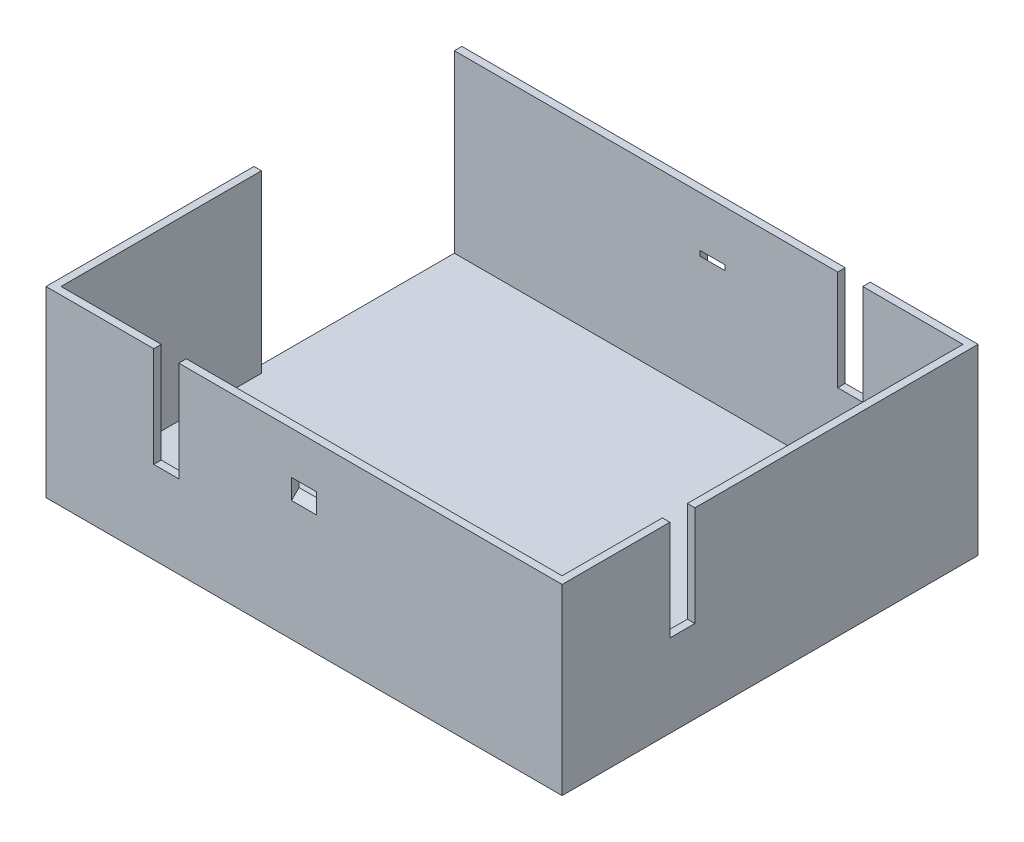
SolidWorks part; units mm, degrees
ref_plane "Front Plane" through (0, 0, 0) normal (0, 0, 1) x (1, 0, 0)
ref_plane "Top Plane" through (0, 0, 0) normal (0, 1, 0) x (1, 0, 0)
ref_plane "Right Plane" through (0, 0, 0) normal (1, 0, 0) x (0, 0, -1)
sketch "Sketch1" plane through (0, 0, 0) normal (0, 1, 0) x (1, 0, 0)
  line L1 (-28.4717, 11.6745) -> (74.5283, 11.6745)
  line L2 (-28.4717, 11.6745) -> (-28.4717, -71.3255)
  line L3 (-28.4717, -71.3255) -> (74.5283, -71.3255)
  line L4 (74.5283, 11.6745) -> (74.5283, -71.3255)
  dimension "D1" = 103
  dimension "D2" = 83
extrude "Boss-Extrude1" add sketch "Sketch1" along normal blind 1.5
sketch "Sketch2" plane through (0, 1.5, 0) normal (0, 1, 0) x (1, 0, 0)
  line L0 (-26.9717, 10.1745) -> (-26.9717, -69.8255)
  line L1 (-28.4717, 11.6745) -> (74.5283, 11.6745)
  line L2 (-28.4717, 11.6745) -> (-28.4717, -71.3255)
  line L3 (-28.4717, -71.3255) -> (74.5283, -71.3255)
  line L4 (74.5283, 11.6745) -> (74.5283, -71.3255)
  line L5 (-26.9717, -69.8255) -> (73.0283, -69.8255)
  line L6 (73.0283, 10.1745) -> (73.0283, -69.8255)
  line L7 (-26.9717, 10.1745) -> (73.0283, 10.1745)
  dimension "D1" = 1.5
extrude "Boss-Extrude2" add sketch "Sketch2" along normal blind 35
sketch "Sketch4" plane through (-28.4717, 0, 0) normal (-1, 0, 0) x (0, 0, 1)
  line L0 (-10.1745, 1.5) -> (69.8255, 1.5) construction
  line L1 (-10.1745, 36.5) -> (29.8255, 36.5)
  line L2 (-10.1745, 36.5) -> (-10.1745, 1.5)
  line L3 (-10.1745, 1.5) -> (29.8255, 1.5)
  line L4 (29.8255, 36.5) -> (29.8255, 1.5)
  dimension "D1" = 40
extrude "Cut-Extrude2" cut sketch "Sketch4" against normal blind 1.5
sketch "Sketch5" plane through (0, 0, 71.3255) normal (0, 0, 1) x (1, 0, 0)
  line L1 (-28.4717, 36.5) -> (74.5283, 36.5) construction
  line L2 (-6.9717, 36.5) -> (-1.9717, 36.5)
  line L3 (-6.9717, 36.5) -> (-6.9717, 16.5)
  line L4 (-6.9717, 16.5) -> (-1.9717, 16.5)
  line L7 (-1.9717, 36.5) -> (-1.9717, 16.5)
  line L8 (-26.9717, 36.5) -> (-26.9717, 1.5) construction
  dimension "D1" = 5
  dimension "D2" = 20
  dimension "D3" = 20
extrude "Cut-Extrude3" cut sketch "Sketch5" against normal blind 1.5
sketch "Sketch6" plane through (74.5283, 0, 0) normal (1, 0, 0) x (0, 0, -1)
  line L0 (-71.3255, 36.5) -> (11.6745, 36.5) construction
  line L1 (-49.8255, 36.5) -> (-44.8255, 36.5)
  line L2 (-49.8255, 36.5) -> (-49.8255, 16.5)
  line L3 (-49.8255, 16.5) -> (-44.8255, 16.5)
  line L4 (-44.8255, 36.5) -> (-44.8255, 16.5)
  line L5 (-69.8255, 36.5) -> (-69.8255, 1.5) construction
  dimension "D1" = 20
  dimension "D2" = 5
  dimension "D3" = 20
extrude "Cut-Extrude4" cut sketch "Sketch6" against normal blind 1.5
ref_plane "Plane1" through (23.0283, 0, 0) normal (1, 0, 0) x (0, 0, -1)
sketch "Sketch7" plane through (23.0283, 0, 0) normal (1, 0, 0) x (0, 0, -1)
  line L0 (-71.3255, 28) -> (-69.8255, 26.5)
  line L1 (-71.3255, 36.5) -> (-71.3255, 0) construction
  line L2 (-69.8255, 36.5) -> (-69.8255, 1.5) construction
  line L3 (-69.8255, 26.5) -> (-69.8255, 25.5)
  line L4 (-69.8255, 25.5) -> (-71.3255, 24)
  line L5 (-71.3255, 36.5) -> (-49.8255, 36.5) construction
  line L6 (-29.8255, 36.5) -> (-29.8255, 1.5) construction
  line L7 (-71.3255, 28) -> (-71.3255, 24)
  line L8 (11.6745, 28) -> (11.6745, 24)
  line L9 (10.1745, 25.5) -> (11.6745, 24)
  line L10 (10.1745, 26.5) -> (10.1745, 25.5)
  line L11 (11.6745, 28) -> (10.1745, 26.5)
  dimension "D1" = 1
  dimension "D2" = 10
  dimension "D3" = 45
extrude "Cut-Extrude5" cut sketch "Sketch7" against normal mid plane 5
sketch "Sketch9" plane through (0, 0, -11.6745) normal (0, 0, -1) x (-1, 0, 0)
  line L0 (-74.5283, 36.5) -> (28.4717, 36.5) construction
  line L1 (-53.0283, 36.5) -> (-48.0283, 36.5)
  line L2 (-53.0283, 36.5) -> (-53.0283, 16.5)
  line L3 (-53.0283, 16.5) -> (-48.0283, 16.5)
  line L4 (-48.0283, 36.5) -> (-48.0283, 16.5)
  line L5 (-73.0283, 36.5) -> (-73.0283, 1.5) construction
  dimension "D1" = 5
  dimension "D2" = 20
  dimension "D3" = 20
extrude "Cut-Extrude6" cut sketch "Sketch9" against normal blind 5
